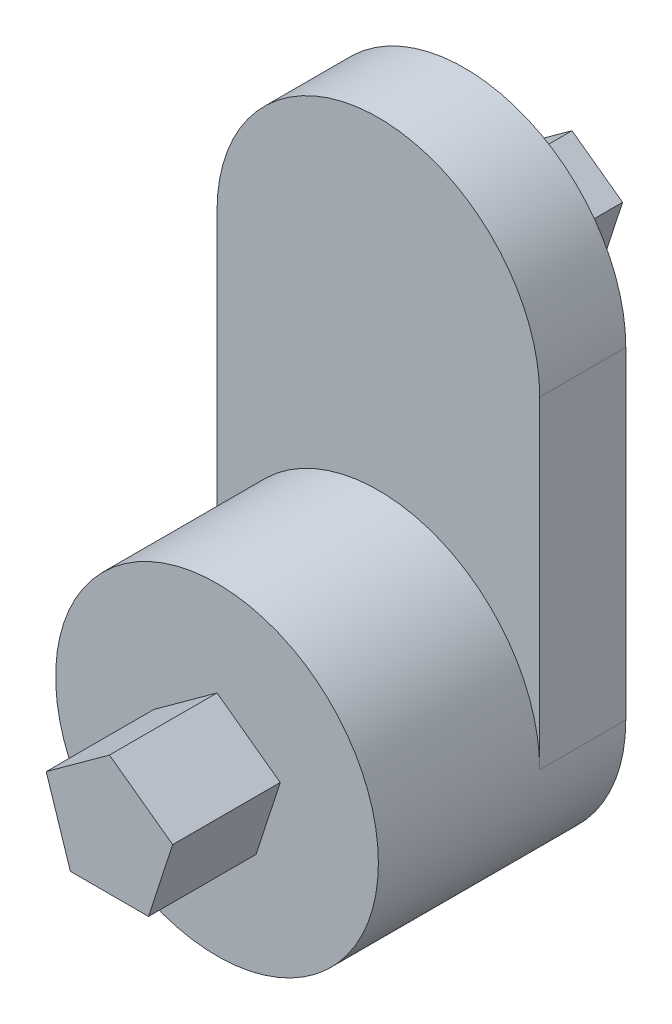
SolidWorks part; units mm, degrees
ref_plane "정면" through (0, 0, 0) normal (0, 0, 1) x (1, 0, 0)
ref_plane "윗면" through (0, 0, 0) normal (0, 1, 0) x (1, 0, 0)
ref_plane "우측면" through (0, 0, 0) normal (1, 0, 0) x (0, 0, -1)
sketch "스케치5" plane through (0, 0, 0) normal (0, 0, 1) x (1, 0, 0)
  circle A0 centre (0, 0) radius 15
  dimension "D1" = 30
extrude "보스-돌출5" add sketch "스케치5" against normal blind 25
sketch "스케치6" plane through (0, 0, -25) normal (0, 0, -1) x (-1, 0, 0)
  line L1 (15, 0) -> (-15, 0)
  line L2 (15, 0) -> (15, 30)
  line L3 (15, 30) -> (-15, 30)
  line L4 (-15, 0) -> (-15, 30)
  circle A0 centre (0, 0) radius 15 construction
  circle A1 centre (0, 0) radius 15
  circle A2 centre (0, 0) radius 15
  arc A3 (15, 30) -> (-15, 30) centre (0, 30) ccw
  circle A4 centre (0, 30) radius 10
  circle M4 centre (0, 0) radius 15
  dimension "D3" = 20
  dimension "D2" = 30
  dimension "D1" = 0
extrude "보스-돌출6" add sketch "스케치6" along normal blind 8 contours L1 M4 | A4 L3 L4 L2 M4 | A4 L3 A3 | A2
sketch "스케치8" plane through (0, 0, -33) normal (0, 0, -1) x (-1, 0, 0)
  circle A0 centre (0, 30) radius 7.5
  dimension "D1" = 15
extrude "보스-돌출7" add sketch "스케치8" along normal blind 5
sketch "스케치16" plane through (0, 0, 0) normal (0, 0, 1) x (1, 0, 0)
  line L1 (0, 6.1803) -> (-5.8779, 1.9098)
  line L2 (-5.8779, 1.9098) -> (-3.6327, -5)
  line L3 (-3.6327, -5) -> (3.6327, -5)
  line L4 (3.6327, -5) -> (5.8779, 1.9098)
  line L5 (5.8779, 1.9098) -> (0, 6.1803)
  circle A0 centre (0, 0) radius 5 construction
  circle A1 centre (0, 0) radius 15 construction
  circle A2 centre (0, 0) radius 15
  dimension "D1" = 10
extrude "컷-돌출1" cut sketch "스케치16" against normal blind 10
sketch "스케치19" plane through (0, 0, -38) normal (0, 0, -1) x (-1, 0, 0)
  line L1 (0, 34.9443) -> (-4.7023, 31.5279)
  line L2 (-4.7023, 31.5279) -> (-2.9062, 26)
  line L3 (-2.9062, 26) -> (2.9062, 26)
  line L4 (2.9062, 26) -> (4.7023, 31.5279)
  line L5 (4.7023, 31.5279) -> (0, 34.9443)
  circle A0 centre (0, 30) radius 4 construction
  dimension "D1" = 8
extrude "보스-돌출14" add sketch "스케치19" along normal blind 5
